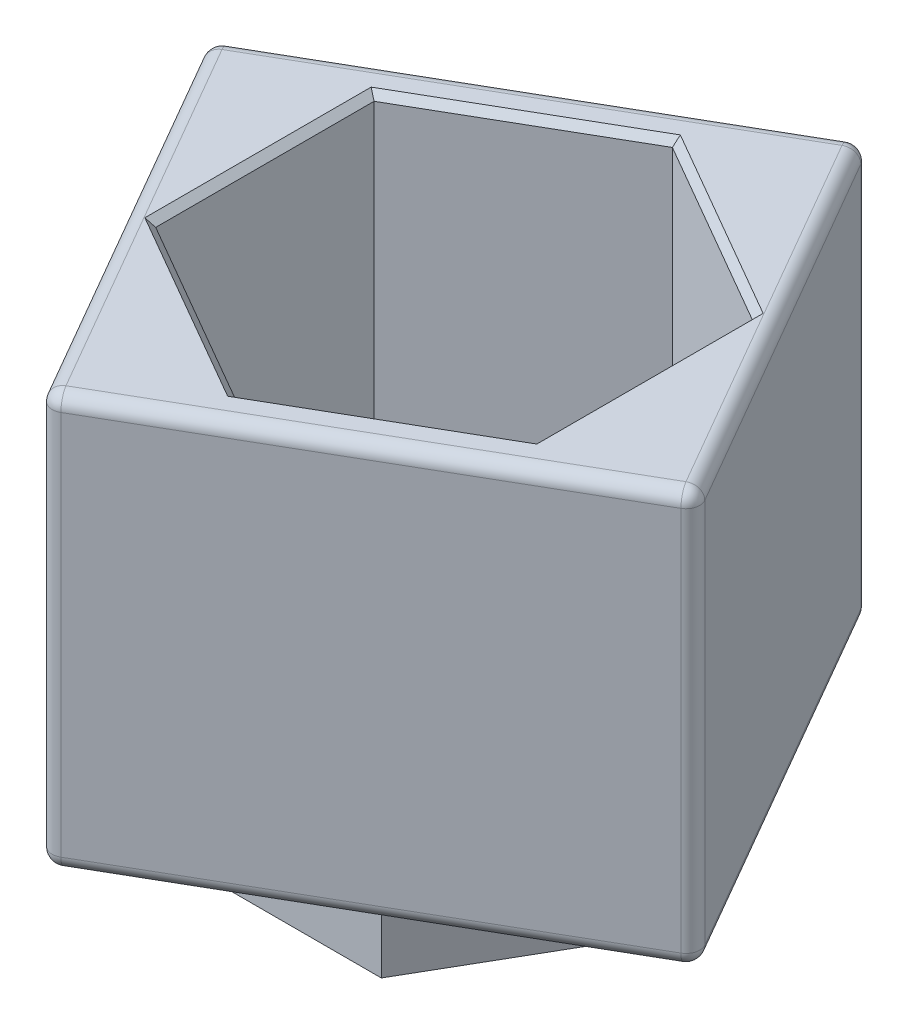
SolidWorks part; units mm, degrees
other "Markup1"
sketch "Sketch1" plane through (0, 0, 0) normal (0.5774, 0.5773, 0.5774) x (0.7071, 0, -0.7071)
sketch "Sketch2" plane through (0, 0, 0) normal (0.5774, 0.5773, 0.5774) x (0.7071, 0, -0.7071)
ref_plane "Front (z)" through (0, 0, 0) normal (0, 0, 1) x (1, 0, 0)
ref_plane "Top (y)" through (0, 0, 0) normal (0, 1, 0) x (1, 0, 0)
ref_plane "Right (x)" through (0, 0, 0) normal (1, 0, 0) x (0, 0, -1)
sketch "Sketch3" plane through (0, 0, 0) normal (0, 1, 0) x (1, 0, 0)
  line L1 (14.4338, 0) -> (7.2169, 12.5)
  line L2 (7.2169, 12.5) -> (-7.2169, 12.5)
  line L3 (-7.2169, 12.5) -> (-14.4338, 0)
  line L4 (-14.4338, 0) -> (-7.2169, -12.5)
  line L5 (-7.2169, -12.5) -> (7.2169, -12.5)
  line L6 (7.2169, -12.5) -> (14.4338, 0)
  circle A0 centre (0, 0) radius 12.5 construction
  dimension "D1" = 25
extrude "Boss-Extrude1" add sketch "Sketch3" along normal blind 5
sketch "Sketch4" plane through (0, 5, 0) normal (0, 1, 0) x (1, 0, 0)
  line L1 (25, -25) -> (-25, -25)
  line L2 (25, -25) -> (25, 25)
  line L3 (25, 25) -> (-25, 25)
  line L4 (-25, -25) -> (-25, 25)
  line L5 (25, -25) -> (-25, 25) construction
  line L6 (25, 25) -> (-25, -25) construction
  point P0 (0, 0)
  dimension "D1" = 50
  dimension "D2" = 50
extrude "Boss-Extrude2" add sketch "Sketch4" along normal blind 30
sketch "Sketch5" plane through (0, 35, 0) normal (0, 1, 0) x (1, 0, 0)
  line L0 (25, -25) -> (25, 25) construction
  line L1 (0, 15.8771) -> (-13.75, 7.9386)
  line L2 (-13.75, 7.9386) -> (-13.75, -7.9386)
  line L3 (-13.75, -7.9386) -> (0, -15.8771)
  line L4 (0, -15.8771) -> (13.75, -7.9386)
  line L5 (13.75, -7.9386) -> (13.75, 7.9386)
  line L6 (13.75, 7.9386) -> (0, 15.8771)
  circle A0 centre (0, 0) radius 13.75 construction
  dimension "D1" = 27.5
extrude "Cut-Extrude1" cut sketch "Sketch5" against normal offset from surface (25 mm away) 5 up to face at (0, 5, 0)
sketch "Sketch6" plane through (0, 0, 0) normal (0, -1, 0) x (1, 0, 0)
  line L0 (-14.4338, 0) -> (-7.2169, 12.5) construction
  line L1 (-12.1244, 0) -> (-6.0622, -10.5)
  line L2 (-6.0622, -10.5) -> (6.0622, -10.5)
  line L3 (6.0622, -10.5) -> (12.1244, 0)
  line L4 (12.1244, 0) -> (6.0622, 10.5)
  line L5 (6.0622, 10.5) -> (-6.0622, 10.5)
  line L6 (-6.0622, 10.5) -> (-12.1244, 0)
  circle A0 centre (0, 0) radius 10.5 construction
  dimension "D1" = 2
extrude "Cut-Extrude2" cut sketch "Sketch6" against normal through all both and the other way through all
sketch "Sketch7" plane through (0, 35, 0) normal (0, 1, 0) x (1, 0, 0)
  line L0 (-25, 25) -> (-25, -25) construction
  line L1 (25, 25) -> (-25, 25) construction
  line L2 (25, -25) -> (25, 25) construction
  line L3 (-25, -25) -> (25, -25) construction
  line L4 (-25, 25) -> (-25, -25)
  line L5 (25, 25) -> (-25, 25)
  line L6 (25, -25) -> (25, 25)
  line L7 (-25, -25) -> (25, -25)
  line L8 (-23.4054, 5.5394) -> (6.9054, 23.0394)
  line L13 (-23.4054, 5.5394) -> (-6.9054, -23.0394)
  line L14 (6.9054, 23.0394) -> (23.4054, -5.5394)
  line L15 (-6.9054, -23.0394) -> (23.4054, -5.5394)
  line L16 (0, 15.8771) -> (-13.75, 7.9386) construction
  line L17 (23.4054, -5.5394) -> (-23.4054, 5.5394) construction
  line L18 (6.9054, 23.0394) -> (-6.9054, -23.0394) construction
  point P8 (0, 0)
  dimension "D1" = 35
  dimension "D2" = 33
extrude "Cut-Extrude3" cut sketch "Sketch7" against normal through all both
fillet "Fillet2" radius 1 12 edges at (-15.1554, 35, 8.75) (-15.1554, 5, 8.75) (-8.25, 35, -14.2894) (-23.4054, 20, -5.5394) (-8.25, 5, -14.2894) (-6.9054, 20, 23.0394) (8.25, 35, 14.2894) (8.25, 5, 14.2894) (23.4054, 20, 5.5394) (15.1554, 35, -8.75) (6.9054, 20, -23.0394) (15.1554, 5, -8.75)
chamfer "Chamfer1" distance 0.5 angle 45 6 edges at (-6.875, 35, 11.9078) (6.875, 35, 11.9078) (13.75, 35, 0) (6.875, 35, -11.9078) (-6.875, 35, -11.9078) (-13.75, 35, 0)
